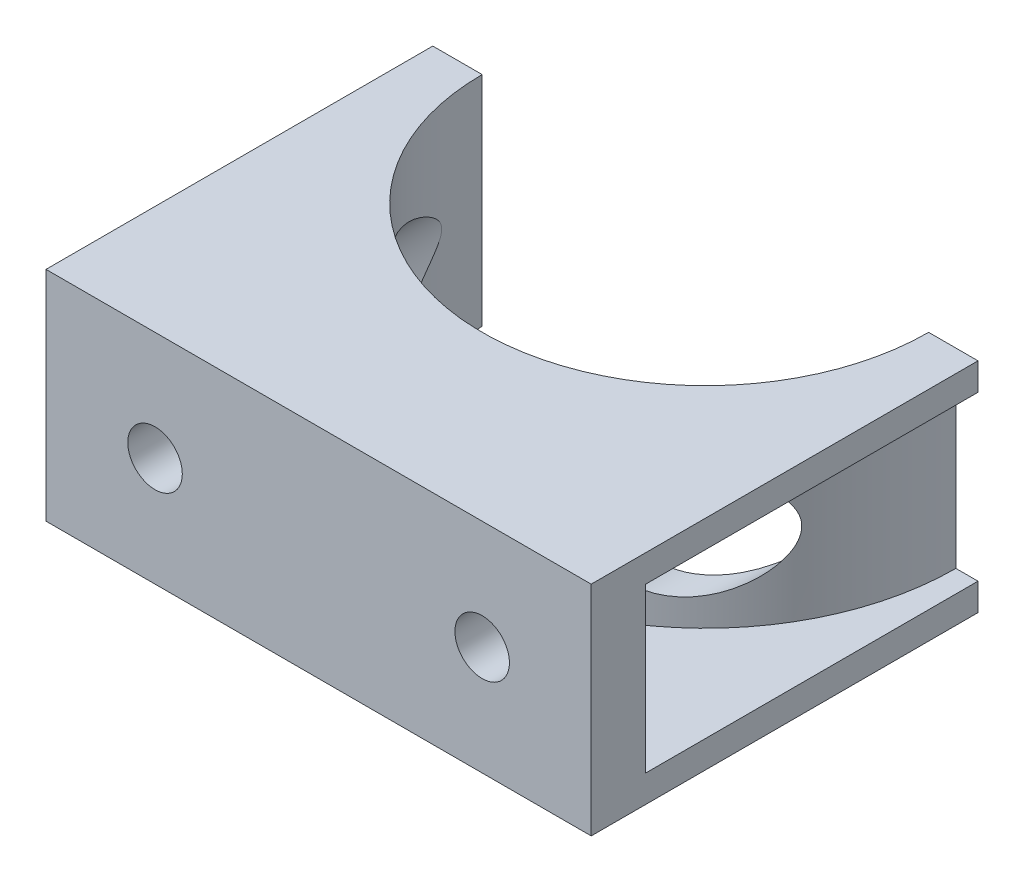
SolidWorks part; units mm, degrees
ref_plane "Front Plane" through (0, 0, 0) normal (0, 0, 1) x (1, 0, 0)
ref_plane "Top Plane" through (0, 0, 0) normal (0, 1, 0) x (1, 0, 0)
ref_plane "Right Plane" through (0, 0, 0) normal (1, 0, 0) x (0, 0, -1)
sketch "Sketch1" plane through (0, 0, 0) normal (0, 1, 0) x (1, 0, 0)
  line L0 (26, 22.525) -> (31.75, 22.525)
  line L1 (-31.75, -22.525) -> (31.75, -22.525)
  line L2 (-31.75, -22.525) -> (-31.75, 22.525)
  line L3 (-31.75, 22.525) -> (-26, 22.525)
  line L4 (31.75, -22.525) -> (31.75, 22.525)
  line L5 (-31.75, -22.525) -> (31.75, 22.525) construction
  line L6 (-31.75, 22.525) -> (31.75, -22.525) construction
  line L7 (-26, 22.525) -> (26, 22.525) construction
  line L8 (-31.75, -3.475) -> (31.75, -3.475) construction
  arc A0 (-26, 22.525) -> (26, 22.525) centre (0, 22.525) ccw
  point P0 (0, 0)
  point P11 (0, 22.525)
  dimension "D1" = 52
  dimension "D3" = 19.05
  dimension "D2" = 63.5
extrude "Boss-Extrude1" add sketch "Sketch1" along normal blind 25.4
sketch "Sketch3" plane through (0, 25.4, 0) normal (0, 1, 0) x (1, 0, 0)
  line L6 (-31.75, -16.175) -> (31.75, -16.175)
  line L7 (-31.75, 22.525) -> (-31.75, -22.525) construction
  line L8 (31.75, -22.525) -> (31.75, 22.525) construction
  line L9 (-31.75, -22.525) -> (31.75, -22.525) construction
  line L10 (-29.175, 22.525) -> (-31.75, 22.525)
  line L11 (-31.75, 22.525) -> (-31.75, -16.175)
  line L12 (29.175, 22.525) -> (31.75, 22.525)
  line L13 (31.75, 22.525) -> (31.75, -16.175)
  arc A0 (-29.175, 22.525) -> (29.175, 22.525) centre (0, 22.525) ccw
  arc A1 (-26, 22.525) -> (26, 22.525) centre (0, 22.525) ccw construction
  dimension "D1" = 3.175
  dimension "D2" = 6.35
extrude "Cut-Extrude3" cut sketch "Sketch3" against normal blind 19.05 from offset 3.175 offset against normal yes
sketch "Sketch5" plane through (0, 0, 22.525) normal (0, 0, 1) x (1, 0, 0)
  line L0 (-31.75, 25.4) -> (-31.75, 0) construction
  line L1 (-31.75, 12.7) -> (31.75, 12.7) construction
  line L2 (31.75, 25.4) -> (31.75, 0) construction
  circle A0 centre (-19.05, 12.7) radius 3.175
  circle A1 centre (19.05, 12.7) radius 3.175
  point P10 (0, 0)
  point P11 (0, 12.7)
  dimension "D3" = 6.35
  dimension "D4" = 6.35
  dimension "D1" = 19.05
  dimension "D2" = 19.05
extrude "Cut-Extrude4" cut sketch "Sketch5" against normal up to surface (6.35 mm away) up to face at (0, 12.7, 16.175)
sketch "Sketch6" plane through (0, 0, -22.525) normal (0, 0, -1) x (-1, 0, 0)
  circle A0 centre (-19.05, 12.7) radius 6.4135
  circle A1 centre (19.05, 12.7) radius 6.4135
  dimension "D1" = 12.827
  dimension "D2" = 12.827
extrude "Cut-Extrude5" cut sketch "Sketch6" against normal up to surface (38.7 mm away) up to face at (-15.875, 12.7, 16.175)
